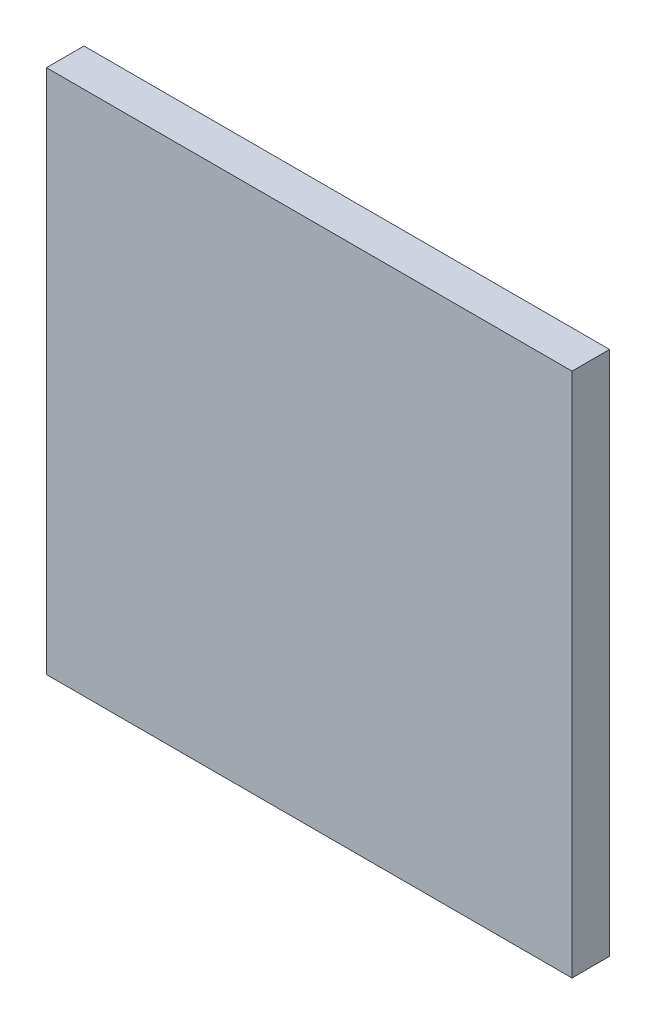
SolidWorks part; units mm, degrees
ref_plane "Front" through (0, 0, 0) normal (0, 0, 1) x (1, 0, 0)
ref_plane "Top" through (0, 0, 0) normal (0, 1, 0) x (1, 0, 0)
ref_plane "Right" through (0, 0, 0) normal (1, 0, 0) x (0, 0, -1)
sketch "Sketch1" plane through (0, 0, 0) normal (0, 0, 1) x (1, 0, 0)
  line L1 (-1.75, -1.75) -> (1.75, -1.75)
  line L2 (-1.75, -1.75) -> (-1.75, 1.75)
  line L3 (-1.75, 1.75) -> (1.75, 1.75)
  line L4 (1.75, -1.75) -> (1.75, 1.75)
  line L5 (-1.75, -1.75) -> (1.75, 1.75) construction
  line L6 (-1.75, 1.75) -> (1.75, -1.75) construction
  point P0 (0, 0)
  dimension "D1" = 3.5
extrude "Boss-Extrude1" add sketch "Sketch1" against normal blind 0.25
